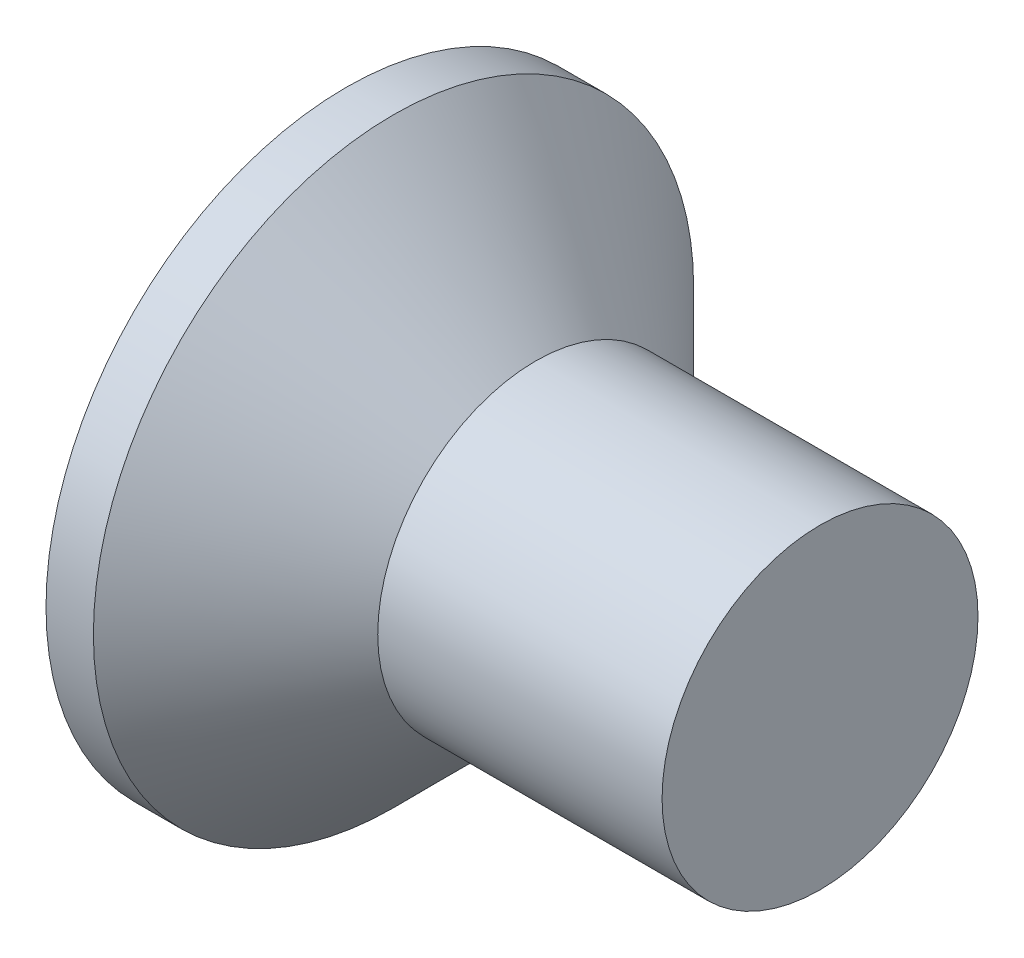
SolidWorks part; units mm, degrees
revolve "Base-Revolve" add sketch "BodySke" angle 360 about L5
sketch "BodySke" plane through (0, 0, 0) normal (0, 0, 1) x (1, 0, 0)
  line L0 (0, 0) -> (0, 1.9)
  line L1 (0, 1.9) -> (0.3, 1.9)
  line L2 (1.2, 1) -> (3, 1)
  line L3 (3, 1) -> (3, 0)
  line L4 (3, 0) -> (0, 0)
  line L5 (-6.35, 0) -> (82.55, 0) construction
  line L6 (1.2, -1) -> (3, -1) construction
  line L7 (0.3, -1.9) -> (1.2, -1) construction
  line L8 (0.3, 1.9) -> (1.2, 1)
  line L9 (0, -1.9) -> (0.3, -1.9) construction
  line L10 (1.6, 2.5875) -> (1.6, -6.9375) construction
  line L11 (0, 6.35) -> (0, -3.175) construction
  dimension "Diameter" = 2
  dimension "Length" = 3
  dimension "Head_ht" = 1.2
  dimension "Head_dia" = 3.8
  dimension "Head_ang" = 90
  dimension "D6" = 0.3
  dimension "Advance" = 0.4
  dimension "Thread_nom" = 3
cosmetic thread "ThreadCosmetic" [suppressed] parameters "Thread_length"=1.4, "Thread_minor"=1.548
extrude "Slot" [suppressed] cut sketch "Sketch2" against normal blind 0.6
sketch "Sketch2" plane through (0, 0, 0) normal (-1, 0, 0) x (0, 0, 1)
  line L0 (-1.9, -0.35) -> (1.9, -0.35)
  line L1 (-1.9, -0.35) -> (-1.9, 0.35)
  line L2 (1.9, 0.35) -> (-1.9, 0.35)
  line L3 (1.9, 0.35) -> (1.9, -0.35)
  dimension "Slot_width" = 0.7
  dimension "D1" = 0.35
  dimension "D2" = 3.8
  dimension "D3" = 1.9
material "Brass"
ref_plane "Plane1" through (0, 0, 0) normal (0, 0, 1) x (1, 0, 0)
ref_plane "Plane2" through (0, 0, 0) normal (0, 1, 0) x (1, 0, 0)
ref_plane "Plane3" through (0, 0, 0) normal (1, 0, 0) x (0, 0, -1)
sketch "Sketch3" plane through (0, 0, 0) normal (-1, 0, 0) x (0, 0, 1)
  line L0 (-0.265, 1.07) -> (0.265, 1.07)
  line L1 (0.265, 1.07) -> (0.265, -1.07)
  line L2 (0.265, -1.07) -> (-0.265, -1.07)
  line L3 (-0.265, -1.07) -> (-0.265, 1.07)
  dimension "Cross_dia" = 2.14
  dimension "Cross_width" = 0.53
  dimension "D1" = 1.07
  dimension "D2" = 0.265
ref_plane "Plane4" through (1.54, 0, 0) normal (-1, 0, 0) x (0, 0, 1)
sketch "Sketch4" plane through (1.54, 0, 0) normal (-1, 0, 0) x (0, 0, 1)
  line L0 (-0.1325, 0.1325) -> (0.1325, 0.1325)
  line L3 (0.1325, 0.1325) -> (0.1325, -0.1325)
  line L4 (0.1325, -0.1325) -> (-0.1325, -0.1325)
  line L5 (-0.1325, -0.1325) -> (-0.1325, 0.1325)
  dimension "D2" = 0.265
  dimension "D1" = 0.265
  dimension "D3" = 0.1325
  dimension "D4" = 0.1325
loft "Cross" cut profiles "Sketch3", "Sketch4"
pattern_circular "CirPattern1" count 2 every 90 about axis through (0, 0, 0) along (1, 0, 0) of "Cross"
sketch "ThdSchSke" plane through (0, 0, 0) normal (0, 0, 1) x (1, 0, 0)
  line L0 (1.6, -0.774) -> (1.4418, -1)
  line L1 (1.6, -0.774) -> (1.7582, -1)
  line L2 (1.7582, -1) -> (1.7582, -1.25)
  line L3 (-3.175, 0) -> (5.1513, 0) construction
  line L5 (1.7582, -1.25) -> (1.4418, -1.25)
  line L6 (1.4418, -1.25) -> (1.4418, -1)
  line L7 (0, 1.9) -> (0, -1.9) construction
  dimension "Diameter" = 2
  dimension "Thread_minor" = 1.548
  dimension "Start" = 1.6
revolve "ThreadSchematic" [suppressed] cut sketch "ThdSchSke" angle 360 about L3
pattern_linear "ThdSchPat" [suppressed]
equation "\"D1@Sketch3\" = \"Cross_dia@Sketch3\" / 2"
equation "\"D2@Sketch3\" = \"Cross_width@Sketch3\" / 2"
equation "\"D1@Sketch4\" = \"Cross_width@Sketch3\" *.5"
equation "\"D2@Sketch4\" = \"D1@Sketch4\""
equation "\"D4@Sketch4\" = \"D2@Sketch4\" / 2"
equation "\"D3@Sketch4\" = \"D1@Sketch4\" / 2"
equation "\"D1@Sketch2\" = \"Slot_width@Sketch2\" / 2"
equation "\"D2@Sketch2\" = \"Head_dia@BodySke\""
equation "\"D3@Sketch2\" = \"D2@Sketch2\" / 2"
equation "\"Thread_length@ThreadCosmetic\" = ((sgn( (\"Length@BodySke\" - \"Advance@BodySke\" - \"Head_ht@BodySke\" ) - \"Thread_nom@BodySke\" )-1)*( (\"Length@BodySke\" - \"Advance@BodySke\" - \"Head_ht@BodySke\" ) - \"Thread_nom@BodySke\" ))/-2+ \"Thread_nom@BodySke\""
equation "\"Thread_minor@ThdSchSke\" = \"Thread_minor@ThreadCosmetic\""
equation "\"Diameter@ThdSchSke\" = \"Diameter@BodySke\""
equation "\"Overcut@ThdSchSke\" = \"Diameter@BodySke\" * 1.25"
equation "\"Start@ThdSchSke\" = 0.000001 + \"Length@BodySke\" - \"Thread_length@ThreadCosmetic\"  '---Countersunk---"
equation "\"Num_threads@ThdSchPat\" = int( \"Thread_length@ThreadCosmetic\" / \"Advance@BodySke\" + 0.999 )  + 1"
equation "\"Advance@ThdSchPat\" = \"Thread_length@ThreadCosmetic\" /  (\"Num_threads@ThdSchPat\" - 1) 'relax it"
